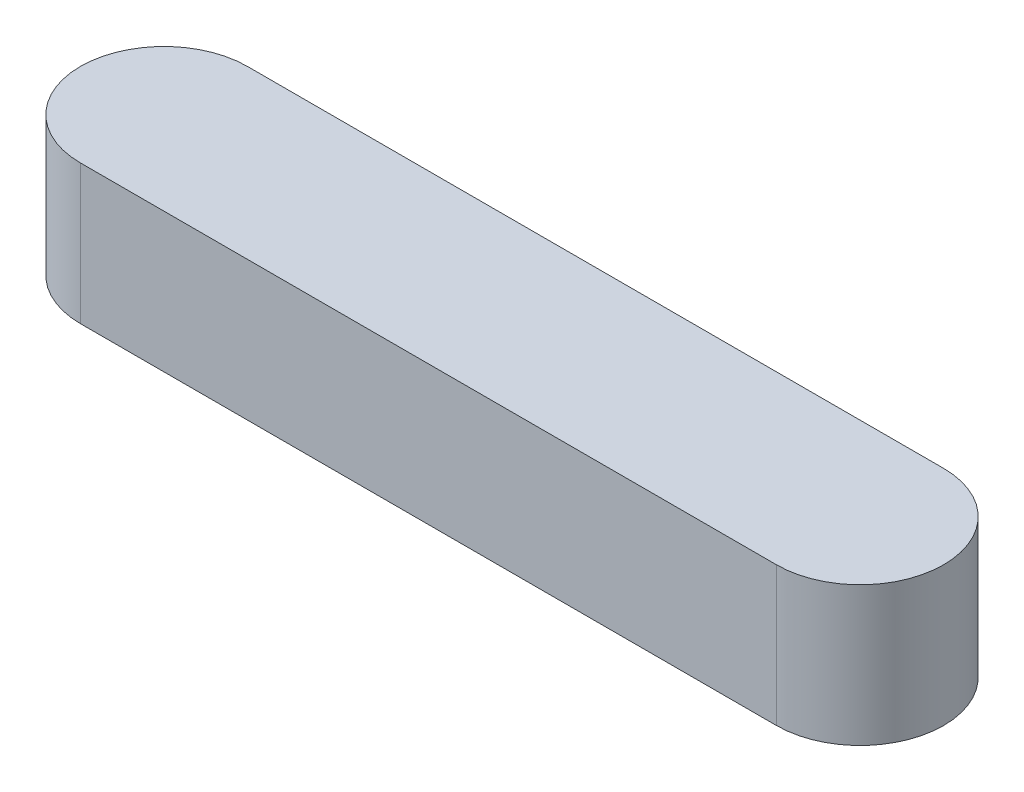
SolidWorks part; units mm, degrees
ref_plane "Plan de face" through (0, 0, 0) normal (0, 0, 1) x (1, 0, 0)
ref_plane "Plan de dessus" through (0, 0, 0) normal (0, 1, 0) x (1, 0, 0)
ref_plane "Plan de droite" through (0, 0, 0) normal (1, 0, 0) x (0, 0, -1)
sketch "Esquisse1" plane through (0, 0, 0) normal (0, 1, 0) x (1, 0, 0)
  line L0 (-21.1781, -15.7729) -> (-46.1781, -15.7729)
  line L1 (-21.1781, -9.7729) -> (-46.1781, -9.7729)
  arc A0 (-21.1781, -9.7729) -> (-21.1781, -15.7729) centre (-21.1781, -12.7729) cw
  arc A1 (-46.1781, -9.7729) -> (-46.1781, -15.7729) centre (-46.1781, -12.7729) ccw
  point P6 (-33.6781, -9.7729)
  dimension "D1" = 25
  dimension "D2" = 6
extrude "Boss.-Extru.1" add sketch "Esquisse1" along normal blind 5 contours L1 A1 L0 A0
